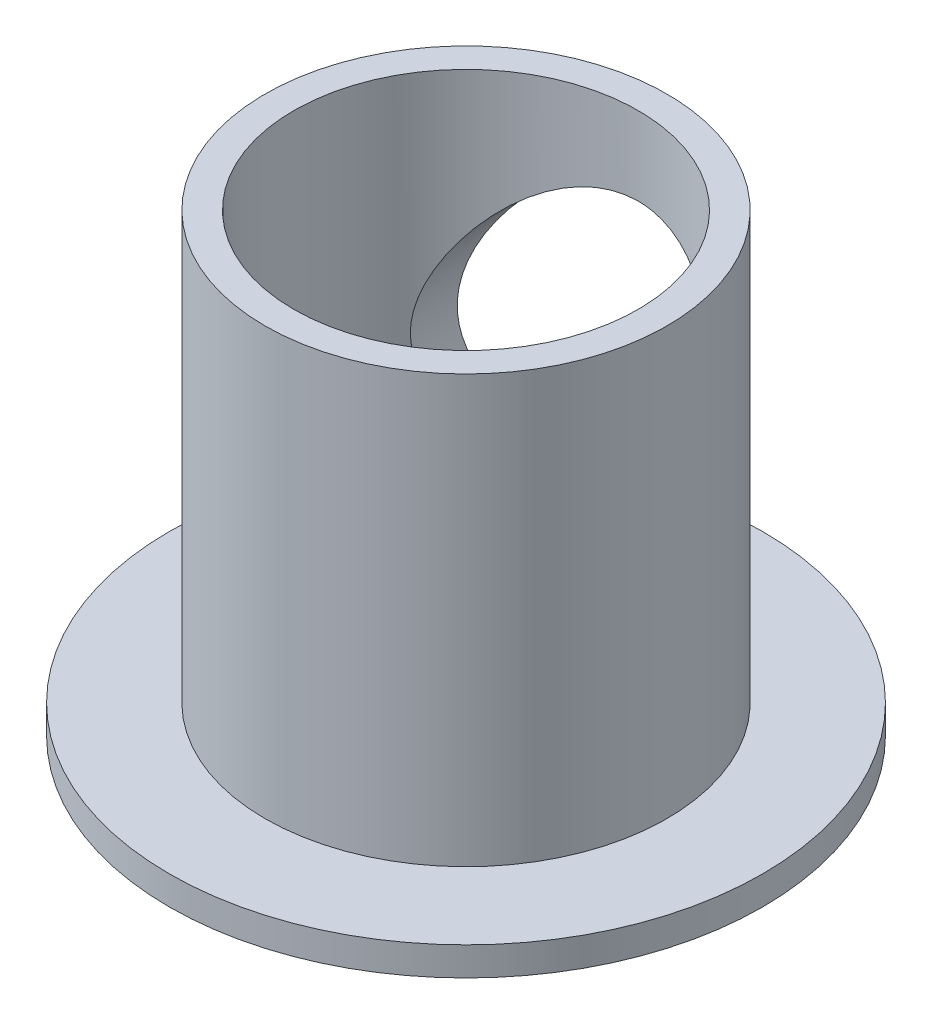
SolidWorks part; units mm, degrees
material "6061-T6 (SS)"
ref_plane "Front" through (0, 0, 0) normal (0, 0, 1) x (1, 0, 0)
ref_plane "Top" through (0, 0, 0) normal (0, 1, 0) x (1, 0, 0)
ref_plane "Right" through (0, 0, 0) normal (1, 0, 0) x (0, 0, -1)
sketch "Sketch1" plane through (0, 0, 0) normal (0, 1, 0) x (1, 0, 0)
  circle A0 centre (0, 0) radius 9
  circle A1 centre (0, 0) radius 10.5
  dimension "D1" = 18
  dimension "D2" = 21
extrude "Boss-Extrude1" add sketch "Sketch1" along normal blind 38.3
sketch "Sketch2" plane through (0, 38.3, 0) normal (0, 1, 0) x (1, 0, 0)
  line L0 (0, 10.5) -> (0, 12.5) construction
  circle A0 centre (0, 0) radius 9 construction
  circle A1 centre (0, 0) radius 9
  circle A2 centre (0, 0) radius 12.5
  circle A3 centre (0, 0) radius 10.5 construction
  circle A37 centre (0, 12.5) radius 1
  circle A38 centre (0, 0) radius 15.5
  point P8 (0, 11.5)
  point P55 (0, 0)
  dimension "D1" = 25
  dimension "D4" = 2
  dimension "D2" = 31
extrude "Boss-Extrude2" add sketch "Sketch2" along normal blind 1.5
ref_plane "Plane1" through (0, 19.15, 0) normal (0, -1, 0) x (-1, 0, 0)
mirror "Mirror1" about plane through (0, 19.15, 0) normal (0, -1, 0) of "Boss-Extrude2"
sketch "Sketch10" plane through (0, 0, 0) normal (0, 0, 1) x (1, 0, 0)
  line L0 (0, 0) -> (0, 10.55) construction
  circle A0 centre (0, 10.55) radius 7.65
  dimension "D2" = 15.3
  dimension "D1" = 10.55
extrude "Cut-Extrude1" cut sketch "Sketch10" against normal through all
sketch "Sketch15" plane through (0, 39.8, 0) normal (0, 1, 0) x (1, 0, 0)
  circle A0 centre (0, 0) radius 20.7553
extrude "Cut-Extrude3" cut sketch "Sketch15" against normal blind 17.5
